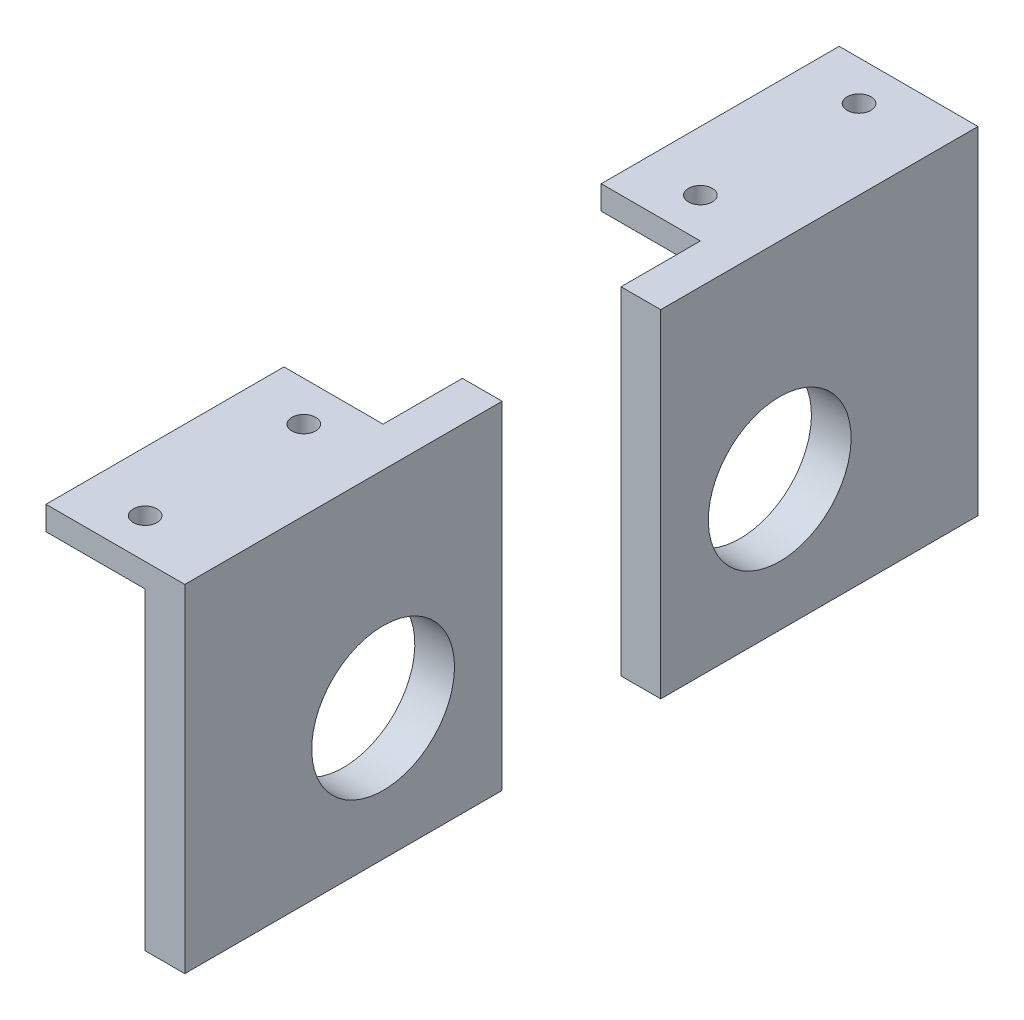
SolidWorks part; units mm, degrees
ref_plane "前视基准面" through (0, 0, 0) normal (0, 0, 1) x (1, 0, 0)
ref_plane "上视基准面" through (0, 0, 0) normal (0, 1, 0) x (1, 0, 0)
ref_plane "右视基准面" through (0, 0, 0) normal (1, 0, 0) x (0, 0, -1)
other "Configuration Table"
sketch "草图1" plane through (0, 0, 0) normal (1, 0, 0) x (0, 0, -1)
  line L0 (-15, -28.5) -> (-15, 11)
  line L2 (-15, 11) -> (15, 11)
  line L4 (-15, -28.5) -> (15, 11) construction
  line L5 (-15, 11) -> (15, -28.5) construction
  line L6 (-15, -28.5) -> (15, -28.5)
  line L8 (15, -28.5) -> (25, -28.5)
  line L9 (25, -28.5) -> (25, -8.5)
  line L12 (15, 11) -> (25, 11)
  line L13 (25, 11) -> (25, -8.5)
  point P0 (0, 0)
  point P2 (0, 0)
extrude "凸台-拉伸1" add sketch "草图1" along normal blind 5 contours L2 L12 L13 L9 L8 L6 L0
sketch3d "3D草图1"
  point P0 (5, -2.7495, 2.7495)
ref_plane "基准面1" through (5, 0, 0) normal (1, 0, 0) x (0, 0, -1)
sketch "草图2" plane through (5, 0, 0) normal (1, 0, 0) x (0, 0, -1)
  circle A0 centre (10, -12) radius 9
extrude "切除-拉伸1" cut sketch "草图2" against normal blind 5
sketch3d "3D草图2"
  point P0 (2.9808, 11, -3.1847)
ref_plane "基准面2" through (0, 11, 0) normal (0, 1, 0) x (1, 0, 0)
sketch "草图3" plane through (0, 11, 0) normal (0, 1, 0) x (1, 0, 0)
  line L0 (5, 15) -> (5, 25)
  line L1 (5, -15) -> (-12.5, -15)
  line L3 (-12.5, 15) -> (-12.5, -15)
  line L4 (5, 15) -> (5, -15)
  line L5 (5, 25) -> (0, 25)
  line L6 (0, 25) -> (0, 15)
  line L7 (0, -15) -> (0, 25) construction
  line L8 (0, 15) -> (-12.5, 15)
extrude "凸台-拉伸2" add sketch "草图3" along normal blind 3
sketch3d "3D草图3"
  point P0 (-6.2094, 14, 4.3134)
ref_plane "基准面4" through (0, 14, 0) normal (0, 1, 0) x (1, 0, 0)
sketch "草图6" plane through (0, 14, 0) normal (0, 1, 0) x (1, 0, 0)
  circle A0 centre (-5, 10) radius 1.5
  circle A1 centre (-5, -10) radius 1.5
extrude "切除-拉伸2" cut sketch "草图6" against normal blind 3
ref_plane "基准面5" through (0, 0, -35) normal (0, 0, -1) x (-1, 0, 0)
mirror "镜向1" about plane through (0, 0, -35) normal (0, 0, -1) of bodies 109
